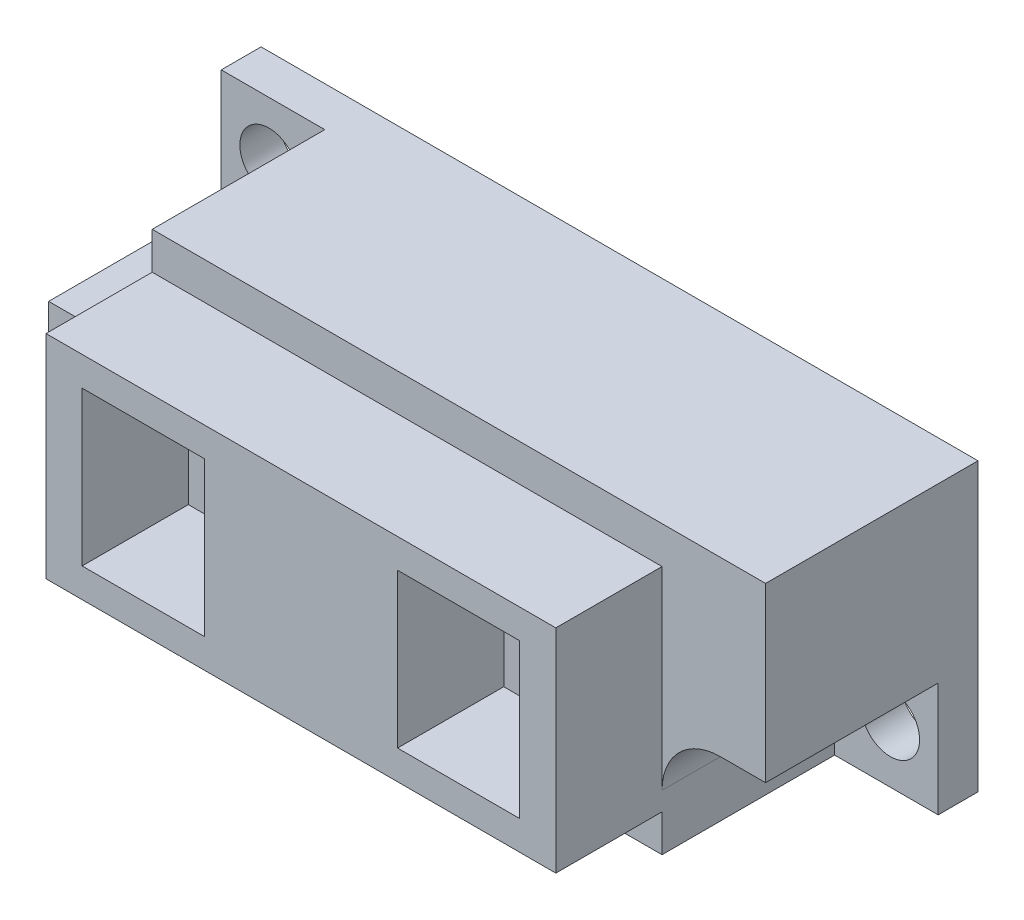
SolidWorks part; units mm, degrees
material "Malleable Cast Iron"
ref_plane "Front Plane" through (0, 0, 0) normal (0, 0, 1) x (1, 0, 0)
ref_plane "Top Plane" through (0, 0, 0) normal (0, 1, 0) x (1, 0, 0)
ref_plane "Right Plane" through (0, 0, 0) normal (1, 0, 0) x (0, 0, -1)
sketch "Sketch1" plane through (0, 0, 0) normal (0, 0, 1) x (1, 0, 0)
  line L1 (-13.5, -5.4) -> (13.5, -5.4)
  line L2 (-13.5, -5.4) -> (-13.5, 5.4)
  line L3 (-13.5, 5.4) -> (13.5, 5.4)
  line L4 (13.5, -5.4) -> (13.5, 5.4)
  line L5 (-13.5, -5.4) -> (13.5, 5.4) construction
  line L6 (-13.5, 5.4) -> (13.5, -5.4) construction
  point P0 (0, 0)
  dimension "D1" = 10.8
  dimension "D2" = 27
extrude "Boss-Extrude1" add sketch "Sketch1" along normal blind 12 contours L3 L4 L1 L2
sketch "Sketch2" plane through (0, 0, 12) normal (0, 0, 1) x (1, 0, 0)
  line L0 (-13.5, 5.4) -> (-13.5, 3.3) construction
  line L1 (-13.5, -5.4) -> (-13.5, 5.4) construction
  line L2 (-13.5, 3.3) -> (-11.7, 3.3) construction
  line L3 (-11.7, 3.3) -> (11.7, 3.3) construction
  line L5 (13.5, -5.4) -> (11.7, -5.4) construction
  line L6 (-13.5, -5.4) -> (13.5, -5.4) construction
  line L7 (11.7, -5.4) -> (11.7, -3.3) construction
  line L8 (11.7, 3.3) -> (11.7, -3.3) construction
  circle A0 centre (-11.7, 3.3) radius 1.1
  circle A1 centre (11.7, -3.3) radius 1.1
  dimension "D3" = 2.2
  dimension "D1" = 2.1
  dimension "D2" = 1.8
  dimension "D4" = 23.4
  dimension "D5" = 2.1
extrude "Cut-Extrude1" cut sketch "Sketch2" against normal through all
sketch "Sketch3" plane through (0, 0, 12) normal (0, 0, 1) x (1, 0, 0)
  line L0 (-13.5, 5.4) -> (-9.6, 5.4) construction
  line L1 (-13.5, 5.4) -> (13.5, 5.4) construction
  line L2 (13.5, -5.4) -> (9.6, -5.4) construction
  line L3 (-13.5, -5.4) -> (13.5, -5.4) construction
  line L4 (9.6, -5.4) -> (9.6, -3.3)
  line L5 (13.5, 5.4) -> (13.5, -1.1) construction
  line L6 (9.6, -5.4) -> (13.5, -5.4)
  line L7 (13.5, -5.4) -> (13.5, 5.4) construction
  line L9 (13.5, -1.1) -> (11.8, -1.1)
  line L11 (-9.6, 5.4) -> (-9.6, 3.3)
  line L13 (-13.5, 5.4) -> (-13.5, 1.1) construction
  line L14 (-13.5, -5.4) -> (-13.5, 5.4) construction
  line L15 (-13.5, 1.1) -> (-11.8, 1.1)
  line L16 (-9.6, 5.4) -> (-13.5, 5.4)
  line L17 (-13.5, 5.4) -> (-13.5, 1.1)
  line L18 (13.5, -1.1) -> (13.5, -5.4)
  arc A0 (9.6, -3.3) -> (11.8, -1.1) centre (11.8, -3.3) cw
  arc A1 (-11.8, 1.1) -> (-9.6, 3.3) centre (-11.8, 3.3) ccw
  dimension "D6" = 2.2
  dimension "D8" = 2.2
  dimension "D1" = 3.9
  dimension "D2" = 3.9
  dimension "D4" = 6.5
  dimension "D7" = 6.5
extrude "Cut-Extrude2" cut sketch "Sketch3" against normal blind 10.5
sketch "Sketch4" plane through (0, 0, 12) normal (0, 0, 1) x (1, 0, 0)
  line L1 (-13.5, -5.4) -> (13.5, -5.4)
  line L2 (-13.5, -5.4) -> (-13.5, 5.4)
  line L3 (-13.5, 5.4) -> (13.5, 5.4)
  line L4 (13.5, -5.4) -> (13.5, 5.4)
  line L5 (-13.5, -5.4) -> (13.5, 5.4) construction
  line L6 (-13.5, 5.4) -> (13.5, -5.4) construction
  line L7 (-9.6, -4) -> (9.6, -4)
  line L8 (-9.6, -4) -> (-9.6, 4)
  line L9 (-9.6, 4) -> (9.6, 4)
  line L10 (9.6, -4) -> (9.6, 4)
  line L11 (-9.6, -4) -> (9.6, 4) construction
  line L12 (-9.6, 4) -> (9.6, -4) construction
  point P0 (0, 0)
  point P7 (0, 0)
  dimension "D1" = 8
  dimension "D2" = 19.2
extrude "Cut-Extrude3" cut sketch "Sketch4" against normal blind 4
sketch "Sketch5" plane through (0, 0, 12) normal (0, 0, 1) x (1, 0, 0)
  line L0 (-5.94, 0) -> (5.94, 0) construction
  line L2 (-8.24, -2.9) -> (-3.64, -2.9)
  line L3 (-8.24, -2.9) -> (-8.24, 2.9)
  line L4 (-8.24, 2.9) -> (-3.64, 2.9)
  line L5 (-3.64, -2.9) -> (-3.64, 2.9)
  line L6 (-8.24, -2.9) -> (-3.64, 2.9) construction
  line L7 (-8.24, 2.9) -> (-3.64, -2.9) construction
  line L8 (3.64, -2.9) -> (8.24, -2.9)
  line L9 (3.64, -2.9) -> (3.64, 2.9)
  line L10 (3.64, 2.9) -> (8.24, 2.9)
  line L11 (8.24, -2.9) -> (8.24, 2.9)
  line L12 (3.64, -2.9) -> (8.24, 2.9) construction
  line L13 (3.64, 2.9) -> (8.24, -2.9) construction
  point P4 (0, 0)
  dimension "D1" = 11.88
  dimension "D2" = 5.8
  dimension "D3" = 4.6
extrude "Cut-Extrude4" cut sketch "Sketch5" against normal blind 4
sketch "Sketch6" plane through (0, 0, 12) normal (0, 0, 1) x (1, 0, 0)
  line L0 (0, 0) -> (-5.94, 0) construction
  line L1 (0, 0) -> (5.94, 0) construction
  dimension "D1" = 5.94
ref_point "Emitter"
ref_point "Detector"
ref_plane "Plane1" through (0, 0, 0) normal (0, 0, -1) x (-1, 0, 0)
sketch "Sketch7" plane through (0, 0, 0) normal (0, 0, -1) x (-1, 0, 0)
  line L1 (13.5, -5.4) -> (3.65, -5.4)
  line L2 (13.5, -5.4) -> (13.5, -7.8)
  line L3 (13.5, -7.8) -> (3.65, -7.8)
  line L4 (3.65, -5.4) -> (3.65, -7.8)
  dimension "D1" = 9.85
  dimension "D2" = 13.2
extrude "Boss-Extrude2" add sketch "Sketch7" along normal blind 2.6 and the other way blind 4
